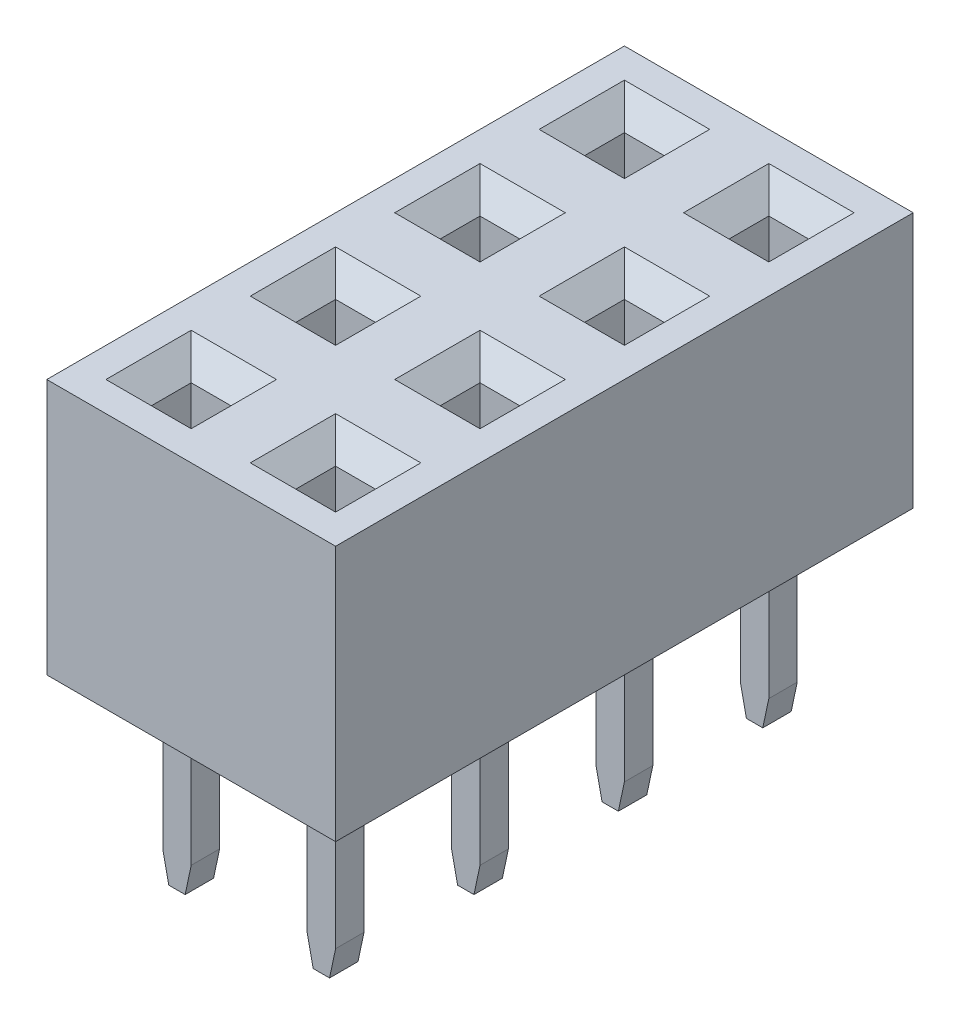
SolidWorks part; units mm, degrees
ref_plane "Спереди" through (0, 0, 0) normal (0, 0, 1) x (1, 0, 0)
ref_plane "Сверху" through (0, 0, 0) normal (0, 1, 0) x (1, 0, 0)
ref_plane "Справа" through (0, 0, 0) normal (1, 0, 0) x (0, 0, -1)
ref_plane "Плоскость1" through (0, 0, 0) normal (0, 1, 0) x (-1, 0, 0)
sketch "Эскиз1" plane through (0, 0, 0) normal (0, 1, 0) x (-1, 0, 0)
  line L0 (0, 0) -> (-5.5295, 0) construction
  line L1 (0, 0) -> (0, -2.1715) construction
  line L2 (-1.27, 1.27) -> (1.27, 1.27)
  line L3 (-1.27, 1.27) -> (-1.27, -1.27)
  line L4 (-1.27, -1.27) -> (1.27, -1.27)
  line L5 (1.27, 1.27) -> (1.27, -1.27)
  point P0 (-1.27, 1.27)
  point P1 (1.27, -1.27)
  point P2 (-1.27, -1.27)
  point P3 (1.27, 1.27)
  dimension "D1" = 2.54
  dimension "D6" = 1.27
extrude "Бобышка-Вытянуть1" add sketch "Эскиз1" along normal blind 4.5
sketch "Эскиз4" plane through (0, 4.5, 0) normal (0, 1, 0) x (1, 0, 0)
  line L0 (0, 0) -> (0.806, 0) construction
  line L1 (0, 0) -> (0, 1.2961) construction
  line L3 (-0.35, 0.35) -> (0.35, 0.35)
  line L4 (-0.35, 0.35) -> (-0.35, -0.35)
  line L5 (-0.35, -0.35) -> (0.35, -0.35)
  line L6 (0.35, 0.35) -> (0.35, -0.35)
  dimension "D1" = 0.7
extrude "Вырез-Вытянуть1" cut sketch "Эскиз4" against normal blind 4.2
chamfer "Фаска3" distance 0.4 angle 45 4 edges at (0.35, 4.5, 0) (0, 4.5, -0.35) (0, 4.5, 0.35) (-0.35, 4.5, 0)
sketch "Эскиз2" plane through (0, 0, 0) normal (0, 1, 0) x (-1, 0, 0)
  line L0 (0, 0) -> (0, -0.4454) construction
  line L1 (0.25, 0.25) -> (-0.25, 0.25)
  line L2 (0.25, 0.25) -> (0.25, -0.25)
  line L3 (0.25, -0.25) -> (-0.25, -0.25)
  line L4 (-0.25, 0.25) -> (-0.25, -0.25)
  line L5 (0, 0) -> (-0.4704, 0) construction
  dimension "D1" = 0.5
  dimension "D2" = 0.5
extrude "Бобышка-Вытянуть2" add sketch "Эскиз2" against normal blind 3.15
chamfer "Фаска2" distance 0.5 angle 12 2 edges at (0.25, -3.15, 0) (-0.25, -3.15, 0)
pattern_linear "Линейный массив1" count 4 spacing 2.54 along (0, 0, -1) count 2 spacing 2.54 along (-1, 0, 0) of "Бобышка-Вытянуть1", "Вырез-Вытянуть1", "Фаска3", "Бобышка-Вытянуть2", "Фаска2"
equation "\"D6@Эскиз1\"=2.54/2"
